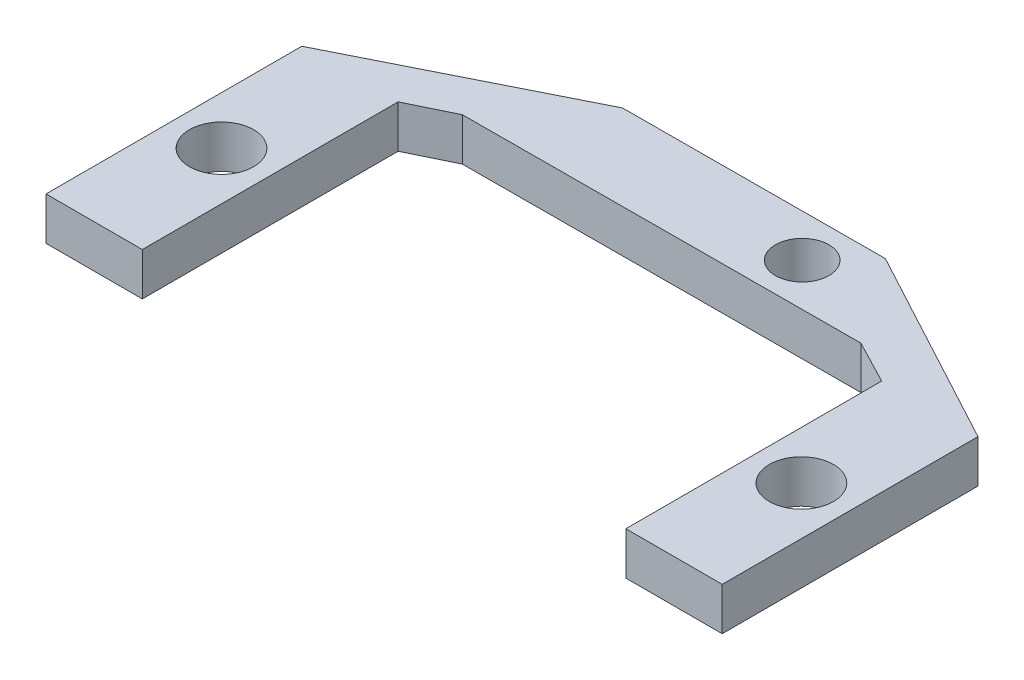
SolidWorks part; units mm, degrees
ref_plane "Front Plane" through (0, 0, 0) normal (0, 0, 1) x (1, 0, 0)
ref_plane "Top Plane" through (0, 0, 0) normal (0, 1, 0) x (1, 0, 0)
ref_plane "Right Plane" through (0, 0, 0) normal (1, 0, 0) x (0, 0, -1)
sketch "Sketch1" plane through (0, 0, 0) normal (0, 1, 0) x (1, 0, 0)
  line L0 (0, 5.4397) -> (0, -5.2419) construction
  line L1 (-21.068, -3.1615) -> (-16.568, -3.1615)
  line L2 (-16.568, -3.1615) -> (-16.568, 8.7885)
  line L3 (-16.568, 8.7885) -> (-14.548, 9.7685)
  line L6 (6.022, 8.7885) -> (6.022, -3.1615)
  line L7 (6.022, -3.1615) -> (10.522, -3.1615)
  line L8 (10.522, -3.1615) -> (10.522, 8.7885)
  line L12 (-21.068, 8.7885) -> (-21.068, -3.1615)
  line L13 (6.022, 8.7885) -> (4.002, 9.8385)
  line L14 (-14.548, 9.7685) -> (4.002, 9.8385)
  line L15 (-21.068, 8.7885) -> (-11.0839, 13.7816)
  line L16 (-11.0839, 13.7816) -> (1.1561, 13.8278)
  line L17 (1.1561, 13.8278) -> (10.522, 8.7885)
  circle A0 centre (-18.818, 2.7885) radius 1.5
  circle A1 centre (8.272, 2.7885) radius 1.5
  circle A2 centre (-0.7239, 11.8207) radius 1.25
  point P19 (-18.818, -3.1615)
  point P20 (8.272, -3.1615)
  dimension "D12" = 3
  dimension "D13" = 3
  dimension "D19" = 2.5
  dimension "D1" = 4.5
  dimension "D2" = 4.5
  dimension "D3" = 11.95
  dimension "D4" = 11.95
  dimension "D5" = 2.02
  dimension "D6" = 0.98
  dimension "D7" = 26.57
  dimension "D8" = 2.02
  dimension "D9" = 5.95
  dimension "D10" = 11.95
  dimension "D11" = 18.55
  dimension "D14" = 5.95
  dimension "D15" = 4
  dimension "D16" = 12.24
  dimension "D17" = 1.05
  dimension "D18" = 2
  dimension "D20" = 11.95
  dimension "D21" = 1.88
extrude "Boss-Extrude1" add sketch "Sketch1" along normal blind 2
